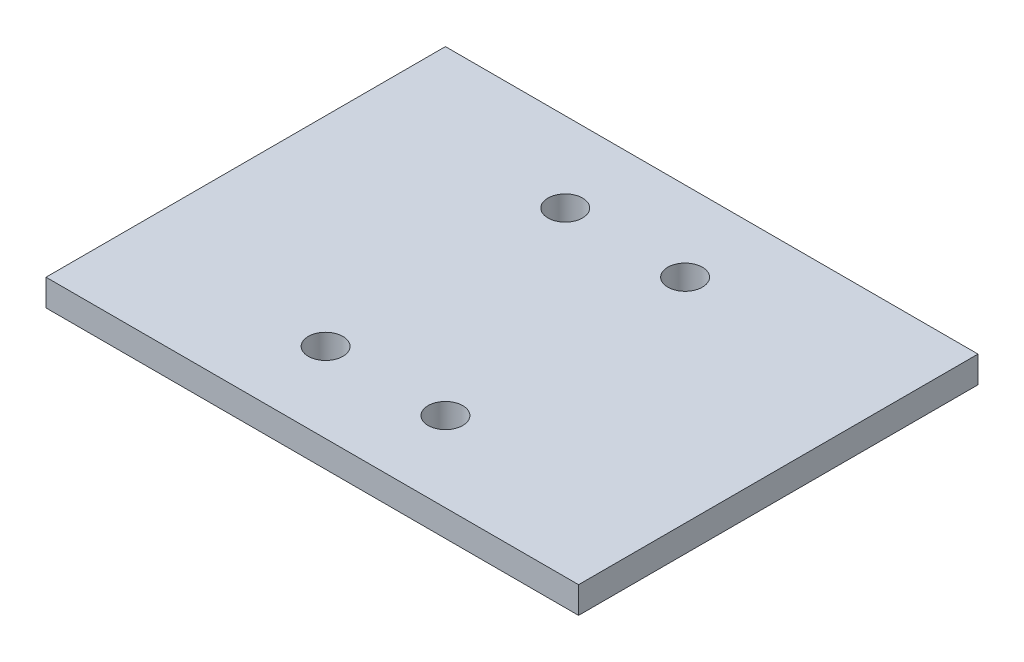
SolidWorks part; units mm, degrees
ref_plane "Front Plane" through (0, 0, 0) normal (0, 0, 1) x (1, 0, 0)
ref_plane "Top Plane" through (0, 0, 0) normal (0, 1, 0) x (1, 0, 0)
ref_plane "Right Plane" through (0, 0, 0) normal (1, 0, 0) x (0, 0, -1)
sketch "Sketch1" plane through (0, 0, 0) normal (0, 1, 0) x (1, 0, 0)
  line L1 (-15, 6) -> (25, 6)
  line L2 (-15, 6) -> (-15, -24)
  line L3 (-15, -24) -> (25, -24)
  line L4 (25, 6) -> (25, -24)
  line L5 (-15, 6) -> (25, -24) construction
  line L6 (-15, -24) -> (25, 6) construction
  circle A5 centre (0, 0) radius 1.3
  circle A6 centre (9, 0) radius 1.3
  circle A7 centre (0, -18) radius 1.3
  circle A8 centre (9, -18) radius 1.3
  point P11 (-0.8749, -0.9615)
  point P17 (5, -9)
  dimension "D1" = 2.6
  dimension "D2" = 2.6
  dimension "D4" = 2.6
  dimension "D6" = 2.6
  dimension "D3" = 9
  dimension "D5" = 18
  dimension "D7" = 30
  dimension "D8" = 40
  dimension "D9" = 15
  dimension "D10" = 6
extrude "Boss-Extrude1" add sketch "Sketch1" along normal blind 2
